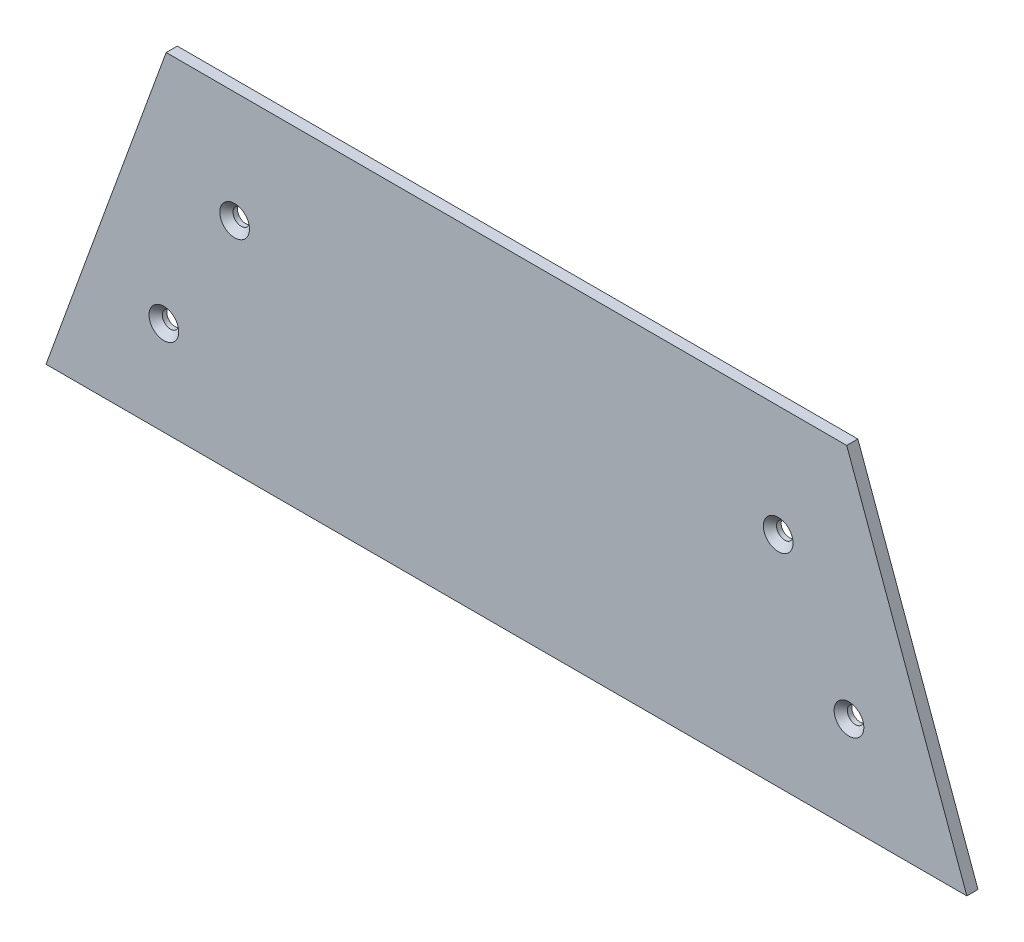
SolidWorks part; units mm, degrees
material "Delrin 2700 NC010, Low Viscosity Acetal Copolymer (SS)"
ref_plane "Front Plane" through (0, 0, 0) normal (0, 0, 1) x (1, 0, 0)
ref_plane "Top Plane" through (0, 0, 0) normal (0, 1, 0) x (1, 0, 0)
ref_plane "Right Plane" through (0, 0, 0) normal (1, 0, 0) x (0, 0, -1)
sketch "Sketch1" plane through (0, 0, 0) normal (0, 0, 1) x (1, 0, 0)
  line L1 (-97.6385, -35) -> (97.6385, -35)
  line L2 (-97.6385, -35) -> (-97.6385, 35)
  line L3 (-97.6385, 35) -> (97.6385, 35)
  line L4 (97.6385, -35) -> (97.6385, 35)
  line L5 (-97.6385, -35) -> (97.6385, 35) construction
  line L6 (-97.6385, 35) -> (97.6385, -35) construction
  point P0 (0, 0)
  dimension "D1" = 70
  dimension "D2" = 195.277
extrude "Main" add sketch "Sketch1" along normal mid plane 2.3622
sketch "Sketch2" plane through (0, 0, 1.1811) normal (0, 0, 1) x (1, 0, 0)
  line L0 (-97.6385, 35) -> (-72.1606, 35)
  line L1 (97.6385, 35) -> (-97.6385, 35) construction
  line L2 (-72.1606, 35) -> (-97.6385, -35)
  line L3 (-97.6385, -35) -> (-97.6385, 35)
  line L4 (97.6385, 35) -> (97.6385, -35)
  line L5 (97.6385, -35) -> (72.1606, 35)
  line L6 (72.1606, 35) -> (97.6385, 35)
  dimension "D1" = 20
  dimension "D2" = 20
extrude "AngleCuts" cut sketch "Sketch2" against normal up to next
hole_wizard "BracketHoles" positions "Sketch3" profile "Sketch4" countersink size "M3" standard "ANSI Metric"
sketch "Sketch3" plane through (0, 0, 1.1811) normal (0, 0, 1) x (1, 0, 0)
  line L0 (-97.6385, -35) -> (97.6385, -35) construction
  point P0 (-72.6378, -15)
  point P2 (-57.6378, 11.3816)
  point P4 (57.6378, 11.3816)
  point P6 (72.6378, -15)
  dimension "D1" = 20
  dimension "D2" = 46.3816
  dimension "D3" = 115.2756
  dimension "D4" = 145.2756
  dimension "D5" = 57.6378
  dimension "D6" = 72.6378
sketch "Sketch4" plane through (-72.6378, -15, 1.1811) normal (1, 0, 0) x (0, -1, 0)
  line L0 (0, 0) -> (0, 5)
  line L1 (0, 5) -> (1.75, 5)
  line L2 (1.75, 5) -> (1.75, 1.4)
  line L3 (1.75, 1.4) -> (3.15, 0)
  line L5 (3.15, 0) -> (0, 0)
  line L6 (-1.75, 1.4) -> (-3.15, 0) construction
  line L10 (0, 5) -> (-1.75, 5) construction
  line L11 (0, -6.35) -> (0, 107.95) construction
  dimension "Hole Dia." = 3.5
  dimension "Hole Depth" = 5
  dimension "Near C'Sink Dia." = 6.3
  dimension "Near C'Sink Angle" = 90
  dimension "Drill Angle" = 180
